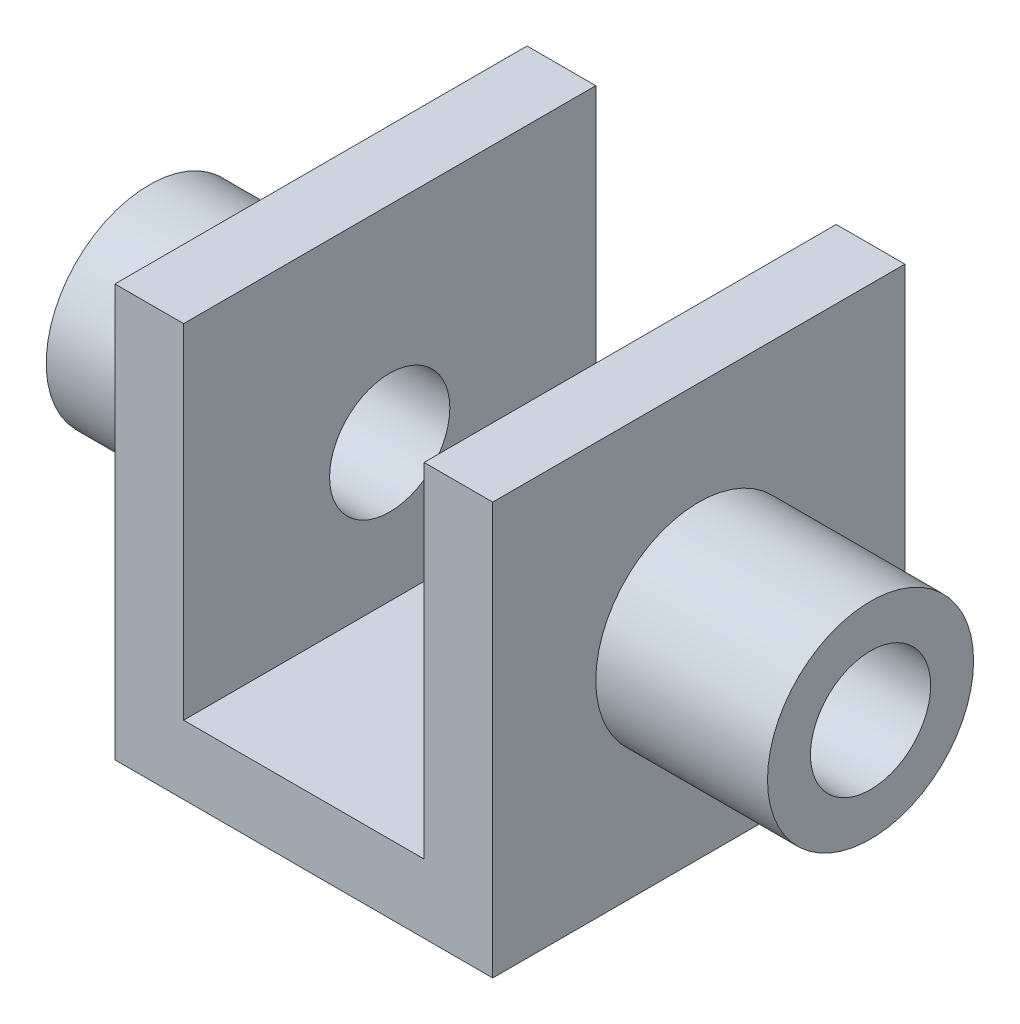
SolidWorks part; units mm, degrees
ref_plane "Front Plane" through (0, 0, 0) normal (0, 0, 1) x (1, 0, 0)
ref_plane "Top Plane" through (0, 0, 0) normal (0, 1, 0) x (1, 0, 0)
ref_plane "Right Plane" through (0, 0, 0) normal (1, 0, 0) x (0, 0, -1)
sketch "Sketch1" plane through (0, 0, 0) normal (0, 0, 1) x (1, 0, 0)
  line L0 (0, 0) -> (44, 0)
  line L1 (44, 0) -> (44, 47.0731)
  line L5 (8, 8) -> (8, 48)
  line L6 (8, 48) -> (0, 48)
  line L7 (0, 48) -> (0, 0)
  line L8 (8, 8) -> (36, 8)
  line L9 (36, 8) -> (36, 48)
  line L10 (36, 48) -> (44, 48)
  line L11 (44, 48) -> (44, 47.0731)
  dimension "D1" = 48
  dimension "D2" = 44
  dimension "D3" = 8
  dimension "D4" = 8
  dimension "D5" = 8
  dimension "D6" = 48
  dimension "D7" = 28
extrude "Boss-Extrude1" add sketch "Sketch1" along normal mid plane 48
sketch "Sketch2" plane through (44, 0, 0) normal (1, 0, 0) x (0, 0, -1)
  circle A0 centre (0, 24) radius 12
  circle A1 centre (0, 24) radius 7
  dimension "D1" = 14
  dimension "D2" = 24
extrude "Boss-Extrude2" add sketch "Sketch2" along normal blind 20
sketch "Sketch3" plane through (44, 0, 0) normal (1, 0, 0) x (0, 0, -1)
  circle A1 centre (0, 24) radius 7
  circle A2 centre (0, 24) radius 7
  dimension "D1" = 0
extrude "Cut-Extrude1" cut sketch "Sketch3" against normal through all and the other way through all
ref_plane "Plane1" through (22, 0, 0) normal (-1, 0, 0) x (0, 0, 1)
mirror "Mirror1" about plane through (22, 0, 0) normal (-1, 0, 0) of "Boss-Extrude2"
